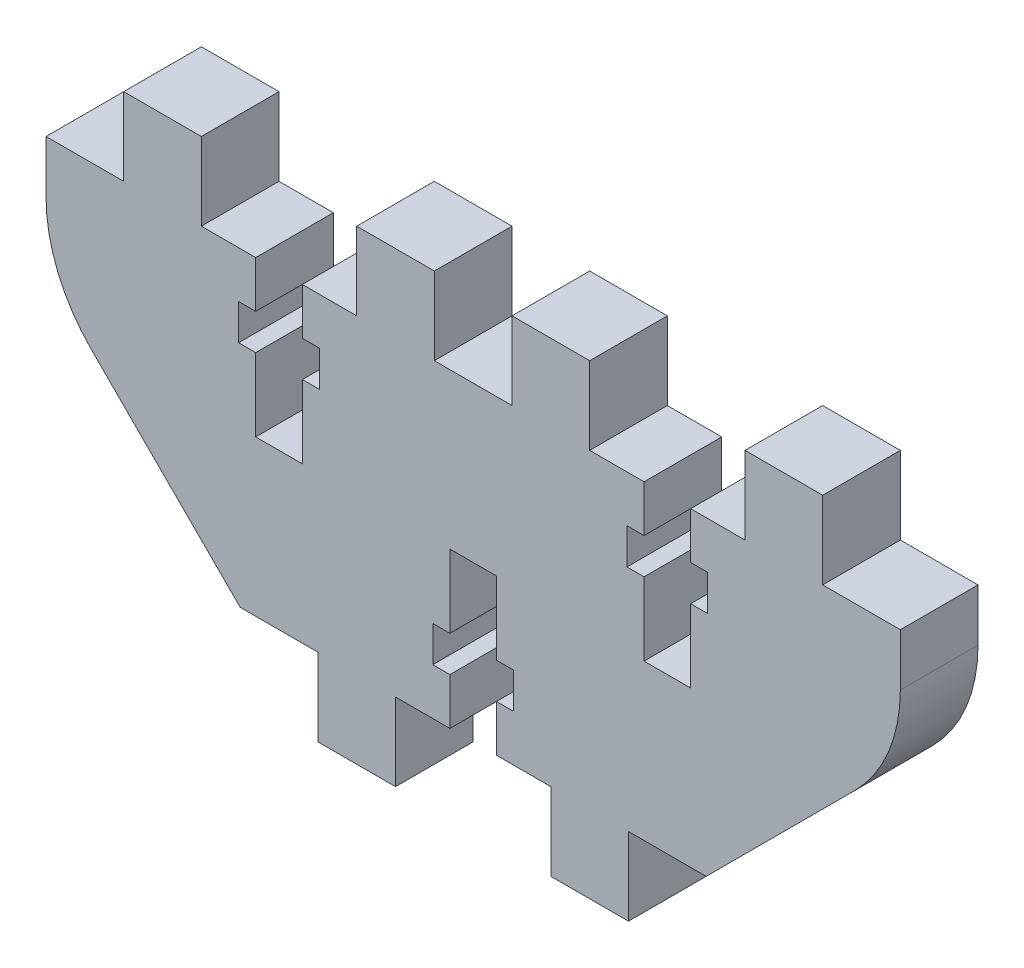
SolidWorks part; units mm, degrees
ref_plane "Plan de face" through (0, 0, 0) normal (0, 0, 1) x (1, 0, 0)
ref_plane "Plan de dessus" through (0, 0, 0) normal (0, 1, 0) x (1, 0, 0)
ref_plane "Plan de droite" through (0, 0, 0) normal (1, 0, 0) x (0, 0, -1)
sketch "Esquisse1" plane through (0, 0, 0) normal (0, 0, 1) x (1, 0, 0)
  line L0 (15, 0) -> (27.5, 12.5)
  line L1 (0, 0) -> (0, -30.9586) construction
  line L2 (-10, 0) -> (-15, 0)
  line L3 (-27.5, 12.5) -> (-27.5, 20)
  line L4 (-15, 0) -> (-27.5, 12.5)
  line L5 (-2.5, 20) -> (2.5, 20)
  line L6 (10, 0) -> (15, 0)
  line L8 (27.5, 12.5) -> (27.5, 20)
  line L9 (27.5, 20) -> (22.5, 20)
  line L10 (-22.5, 20) -> (-27.5, 20)
  line B0 (-2.6, 3) -> (-2.6, 5.3)
  line B1 (1.5, 5.3) -> (1.5, 10)
  line B2 (-1.5, 10) -> (-1.5, 5.3)
  line B3 (-2.6, 5.3) -> (-1.5, 5.3)
  line B4 (0, 0) -> (0, 11.2208) construction
  line B5 (-1.5, 0) -> (-5, 0)
  line B6 (-5, -5) -> (-10, -5)
  line B7 (-10, -5) -> (-10, 0)
  line B8 (-5, -5) -> (-5, 0)
  line B9 (1.5, 0) -> (5, 0)
  line B10 (5, 0) -> (5, -5)
  line B11 (5, -5) -> (10, -5)
  line B12 (10, -5) -> (10, 0)
  line B13 (-1.5, 0) -> (1.5, 0) construction
  line B14 (1.5, 0) -> (1.5, 3)
  line B15 (1.5, 5.3) -> (2.6, 5.3)
  line B16 (2.6, 3) -> (1.5, 3)
  line B17 (1.5, 10) -> (-1.5, 10)
  line B18 (-1.5, 3) -> (-2.6, 3)
  line B19 (2.6, 5.3) -> (2.6, 3)
  line B20 (-1.5, 3) -> (-1.5, 0)
  line B21 (0, 10) -> (0, 0) construction
  line B22 (15.1, 17) -> (15.1, 14.7)
  line B23 (11, 14.7) -> (11, 10)
  line B24 (14, 10) -> (14, 14.7)
  line B25 (15.1, 14.7) -> (14, 14.7)
  line B26 (12.5, 20) -> (12.5, 8.7792) construction
  line B27 (14, 20) -> (17.5, 20)
  line B28 (17.5, 25) -> (22.5, 25)
  line B29 (22.5, 25) -> (22.5, 20)
  line B30 (17.5, 25) -> (17.5, 20)
  line B31 (11, 20) -> (7.5, 20)
  line B32 (7.5, 20) -> (7.5, 25)
  line B33 (7.5, 25) -> (2.5, 25)
  line B34 (2.5, 25) -> (2.5, 20)
  line B35 (14, 20) -> (11, 20) construction
  line B36 (11, 20) -> (11, 17)
  line B37 (11, 14.7) -> (9.9, 14.7)
  line B38 (9.9, 17) -> (11, 17)
  line B39 (11, 10) -> (14, 10)
  line B40 (14, 17) -> (15.1, 17)
  line B41 (9.9, 14.7) -> (9.9, 17)
  line B42 (14, 17) -> (14, 20)
  line B43 (12.5, 10) -> (12.5, 20) construction
  line B44 (-15.1, 17) -> (-15.1, 14.7)
  line B45 (-11, 14.7) -> (-11, 10)
  line B46 (-14, 10) -> (-14, 14.7)
  line B47 (-15.1, 14.7) -> (-14, 14.7)
  line B48 (-12.5, 20) -> (-12.5, 8.7792) construction
  line B49 (-14, 20) -> (-17.5, 20)
  line B50 (-17.5, 25) -> (-22.5, 25)
  line B51 (-22.5, 25) -> (-22.5, 20)
  line B52 (-17.5, 25) -> (-17.5, 20)
  line B53 (-11, 20) -> (-7.5, 20)
  line B54 (-7.5, 20) -> (-7.5, 25)
  line B55 (-7.5, 25) -> (-2.5, 25)
  line B56 (-2.5, 25) -> (-2.5, 20)
  line B57 (-14, 20) -> (-11, 20) construction
  line B58 (-11, 20) -> (-11, 17)
  line B59 (-11, 14.7) -> (-9.9, 14.7)
  line B60 (-9.9, 17) -> (-11, 17)
  line B61 (-11, 10) -> (-14, 10)
  line B62 (-14, 17) -> (-15.1, 17)
  line B63 (-9.9, 14.7) -> (-9.9, 17)
  line B64 (-14, 17) -> (-14, 20)
  line B65 (-12.5, 10) -> (-12.5, 20) construction
  dimension "D1" = 5
  dimension "D2" = 0
  dimension "D3" = 5
  dimension "D4" = 20
sketch_block_instance "Insert M3 plots ep 5mm-1"
sketch_block "Insert M3 plots ep 5mm" parameters "D1"=10, "D2"=5, "D3"=5
sketch_block_instance "Decoupe Insert M3-4"
sketch_block "Decoupe Insert M3" parameters "D1"=5.2, "D2"=3, "D3"=2.3, "D4"=3, "D5"=10
sketch_block_instance "Insert M3 plots ep 5mm-3"
sketch_block_instance "Insert M3 plots ep 5mm-4"
extrude "Boss.-Extru.1" add sketch "Esquisse1" along normal blind 5
fillet "Congé1" radius 10 2 edges at (-27.5, 12.5, 2.5) (27.5, 12.5, 2.5)
